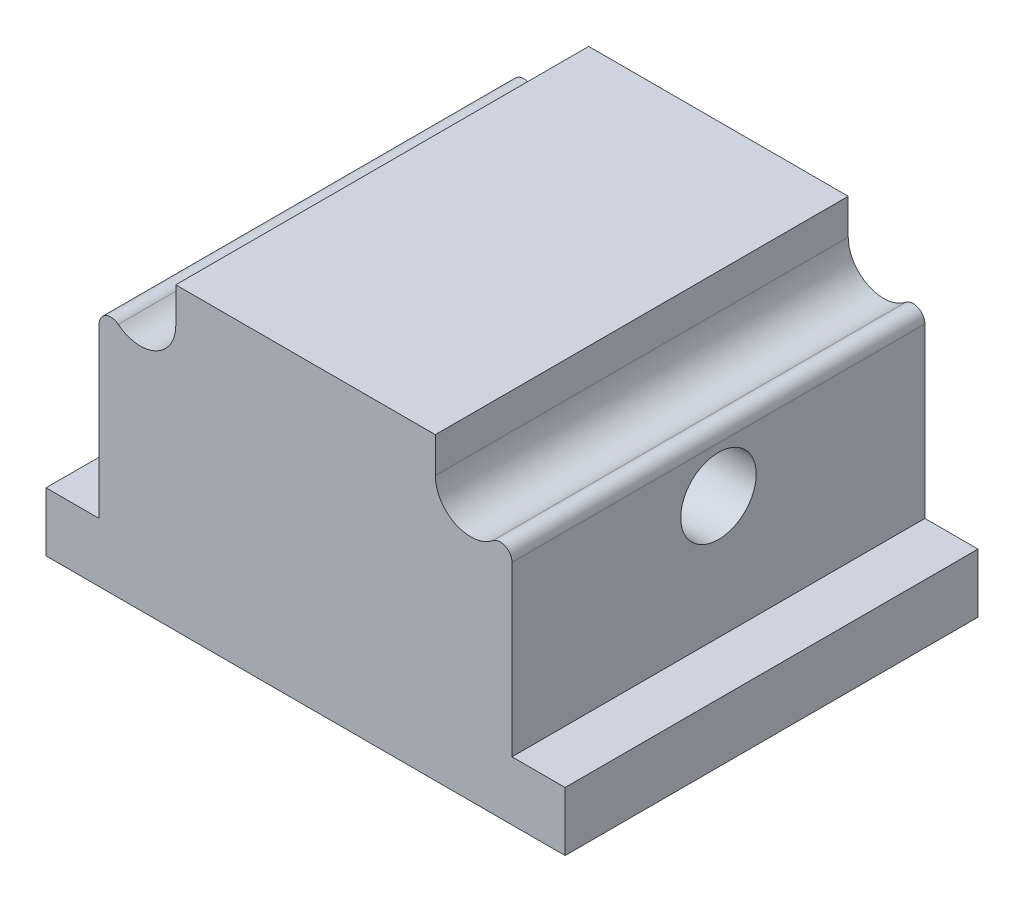
SolidWorks part; units mm, degrees
material "PLA"
ref_plane "前视基准面" through (0, 0, 0) normal (0, 0, 1) x (1, 0, 0)
ref_plane "上视基准面" through (0, 0, 0) normal (0, 1, 0) x (1, 0, 0)
ref_plane "右视基准面" through (0, 0, 0) normal (1, 0, 0) x (0, 0, -1)
sketch "草图1" plane through (0, 0, 0) normal (0, 1, 0) x (1, 0, 0)
  line L1 (-8.75, -8.75) -> (8.75, -8.75)
  line L2 (-8.75, -8.75) -> (-8.75, 8.75)
  line L3 (-8.75, 8.75) -> (8.75, 8.75)
  line L4 (8.75, -8.75) -> (8.75, 8.75)
  line L5 (0, 8.75) -> (0, -8.75) construction
  line L6 (-8.75, 0) -> (8.75, 0) construction
  point P0 (0, 0)
  dimension "D1" = 17.5
extrude "凸台-拉伸1" add sketch "草图1" along normal mid plane 10
sketch "草图3" plane through (8.75, 0, 0) normal (1, 0, 0) x (0, 0, -1)
  circle A0 centre (0, 0) radius 1.6
  dimension "D1" = 3.2
extrude "切除-拉伸1" cut sketch "草图3" against normal through all
sketch "草图4" plane through (0, 0, -8.75) normal (0, 0, -1) x (-1, 0, 0)
  line L0 (-8.75, -5) -> (8.75, -5) construction
  line L1 (0, 0) -> (0, 5) construction
  line L2 (-8.75, 5) -> (8.75, 5) construction
  line L5 (5.5, 3.5) -> (5.5, 5)
  line L6 (5.5, 5) -> (8.5, 5)
  line L8 (7, 5) -> (7, 3.5) construction
  line L9 (5.5, 4.25) -> (8.5, 4.25) construction
  line L12 (-5.5, 5) -> (-8.5, 5)
  line L17 (8.75, 5) -> (8.75, 1.9388)
  line L18 (8.75, 5) -> (8.5, 5)
  line L19 (-5.5, 3.5) -> (-5.5, 5)
  line L22 (-8.75, 5) -> (-8.5, 5)
  line L25 (-8.75, 5) -> (-8.75, 1.9388)
  line L26 (-8.75, 5) -> (-8.75, -5) construction
  arc A2 (5.5, 3.5) -> (7.9375, 2.3291) centre (7, 3.5) ccw
  arc A4 (-5.5, 3.5) -> (-7.9375, 2.3291) centre (-7, 3.5) cw
  arc A5 (-7.9375, 2.3291) -> (-8.75, 1.9388) centre (-8.25, 1.9388) ccw
  arc A6 (7.9375, 2.3291) -> (8.75, 1.9388) centre (8.25, 1.9388) cw
  point P10 (8.5, 5)
  point P17 (-8.75, 2.5964)
  point P21 (-8.75, 2.2459)
  point P27 (-8.75, 2.1337)
  point P30 (-8.5, 5)
  point P31 (-8.75, 5)
  point P171 (7, 4.25)
  dimension "D2" = 1.5
  dimension "D4" = 0.5
  dimension "D1" = 8.5
  dimension "D3" = 14
extrude "切除-拉伸2" cut sketch "草图4" against normal through all
sketch "草图6" plane through (0, -5, 0) normal (0, -1, 0) x (1, 0, 0)
  line L4 (8.75, -8.75) -> (8.75, 8.75)
  line L5 (8.75, 8.75) -> (-8.75, 8.75)
  line L6 (-8.75, 8.75) -> (-8.75, -8.75)
  line L7 (-8.75, -8.75) -> (8.75, -8.75)
  line L8 (8.75, -8.75) -> (8.75, 8.75)
  line L9 (8.75, 8.75) -> (-8.75, 8.75)
  line L10 (-8.75, 8.75) -> (-8.75, -8.75)
  line L11 (-8.75, -8.75) -> (8.75, -8.75)
  dimension "D1" = 0
extrude "凸台-拉伸2" add sketch "草图6" along normal blind 0.2
sketch "草图7" plane through (0, -5.2, 0) normal (0, -1, 0) x (1, 0, 0)
  line L0 (-8.75, -8.75) -> (8.75, -8.75) construction
  line L1 (-11, 8.75) -> (11, 8.75)
  line L2 (-11, 8.75) -> (-11, -8.75)
  line L3 (-11, -8.75) -> (11, -8.75)
  line L4 (11, 8.75) -> (11, -8.75)
  line L5 (0, -8.75) -> (0, 8.75) construction
  line L6 (-11, 0) -> (11, 0) construction
  point P0 (0, 0)
  dimension "D1" = 22
extrude "凸台-拉伸3" add sketch "草图7" along normal blind 2.5
sketch "草图8" plane through (0, -7.7, 0) normal (0, -1, 0) x (1, 0, 0)
  line L0 (0, 0) -> (-8, 0) construction
  line L1 (-8, 0) -> (-2.4721, -7.6085) construction
  line L2 (-2.4721, -7.6085) -> (6.4721, -4.7023) construction
  line L3 (6.4721, -4.7023) -> (6.4721, 4.7023) construction
  line L4 (6.4721, 4.7023) -> (-2.4721, 7.6085) construction
  line L5 (-2.4721, 7.6085) -> (-8, 0) construction
  line L6 (-8, 0) -> (6.4721, -4.7023)
  line L7 (-2.4721, 7.6085) -> (6.4721, -4.7023)
  line L8 (6.4721, 4.7023) -> (-2.4721, -7.6085)
  line L9 (-2.4721, 7.6085) -> (-2.4721, -7.6085)
  line L10 (-8, 0) -> (6.4721, 4.7023)
  circle A0 centre (0, 0) radius 6.4721 construction
  dimension "D1" = 8
extrude "切除-拉伸3" cut sketch "草图8" against normal blind 1.5 contours L10 L6 L9 | L10 L9 L6 L8 L7 | L9 L10 L7 | L10 L7 L8 | L7 L8 L6 | L6 L9 L8
